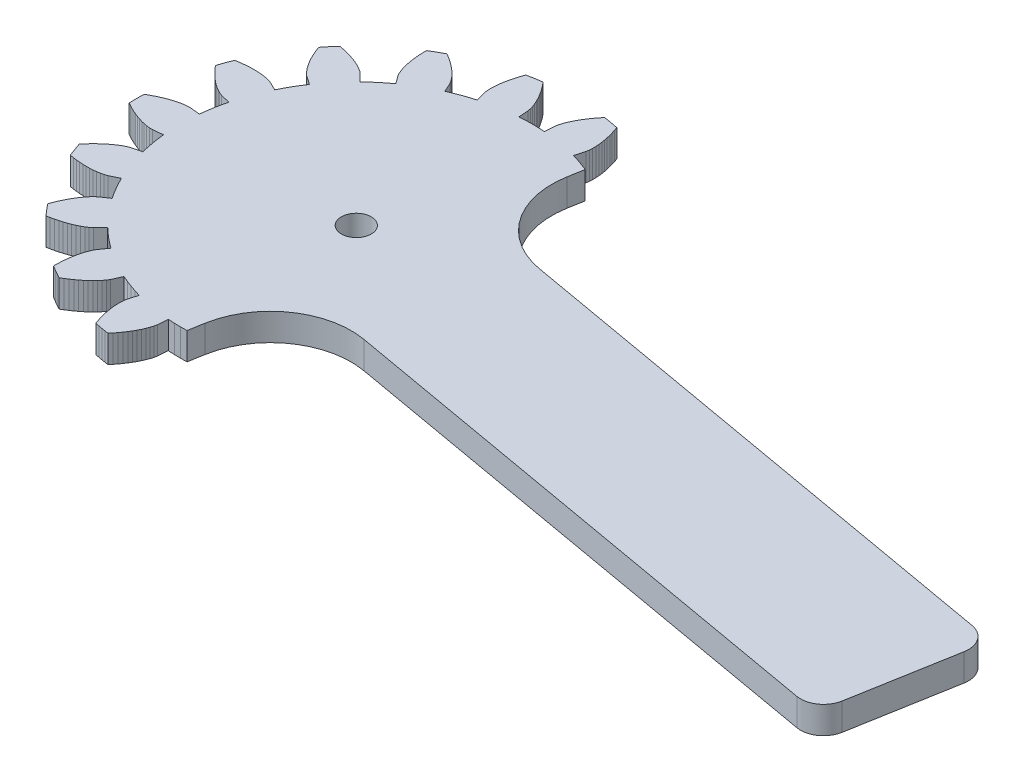
SolidWorks part; units mm, degrees
ref_plane "Front Plane" through (0, 0, 0) normal (0, 0, 1) x (1, 0, 0)
ref_plane "Top Plane" through (0, 0, 0) normal (0, 1, 0) x (1, 0, 0)
ref_plane "Right Plane" through (0, 0, 0) normal (1, 0, 0) x (0, 0, -1)
sketch "Sketch1" plane through (0, 0, 0) normal (0, 1, 0) x (1, 0, 0)
  line L0 (28.4037, 11.9497) -> (144.4799, -8.5177)
  line L1 (148.6006, -14.4026) -> (144.5649, -37.2904)
  line L2 (138.6799, -41.411) -> (22.6037, -20.9437)
  line L3 (0, 0) -> (10.8938, 15.0372) construction
  line L4 (0, 0) -> (5.0938, -17.8562) construction
  line L5 (2.0063, -35.3661) -> (1.4038, -38.7829)
  line L156 (1.4038, -38.7829) -> (0, -38.8083)
  line L157 (0, -38.8083) -> (-1.4038, -38.7829)
  line L158 (-1.4038, -38.7829) -> (-2.8058, -38.7068)
  line L159 (-2.8058, -38.7068) -> (-2.9662, -40.919)
  line L160 (-2.9662, -40.919) -> (-3.0985, -41.5915)
  line L161 (-3.0985, -41.5915) -> (-3.3017, -42.2583)
  line L162 (-3.3017, -42.2583) -> (-3.5532, -42.9207)
  line L163 (-3.5532, -42.9207) -> (-3.8453, -43.5786)
  line L164 (-3.8453, -43.5786) -> (-4.1736, -44.2318)
  line L165 (-4.1736, -44.2318) -> (-4.5353, -44.88)
  line L166 (-4.5353, -44.88) -> (-4.9286, -45.523)
  line L167 (-4.9286, -45.523) -> (-5.3519, -46.1601)
  line L168 (-5.3519, -46.1601) -> (-5.8039, -46.7911)
  line L169 (-5.8039, -46.7911) -> (-6.2839, -47.4155)
  line L170 (-6.2839, -47.4155) -> (-6.7909, -48.0328)
  line L171 (-6.7909, -48.0328) -> (-7.6084, -47.91)
  line L172 (-7.6084, -47.91) -> (-8.4237, -47.7734)
  line L173 (-8.4237, -47.7734) -> (-9.2366, -47.623)
  line L174 (-9.2366, -47.623) -> (-10.0468, -47.4587)
  line L175 (-10.0468, -47.4587) -> (-10.3121, -46.7052)
  line L176 (-10.3121, -46.7052) -> (-10.5496, -45.9543)
  line L177 (-10.5496, -45.9543) -> (-10.7586, -45.2068)
  line L178 (-10.7586, -45.2068) -> (-10.9384, -44.4633)
  line L179 (-10.9384, -44.4633) -> (-11.0881, -43.7246)
  line L180 (-11.0881, -43.7246) -> (-11.2063, -42.9917)
  line L181 (-11.2063, -42.9917) -> (-11.2914, -42.2656)
  line L182 (-11.2914, -42.2656) -> (-11.3408, -41.5475)
  line L183 (-11.3408, -41.5475) -> (-11.3506, -40.8391)
  line L184 (-11.3506, -40.8391) -> (-11.3135, -40.143)
  line L185 (-11.3135, -40.143) -> (-11.2079, -39.4658)
  line L186 (-11.2079, -39.4658) -> (-10.6019, -37.3321)
  line L187 (-10.6019, -37.3321) -> (-11.9454, -36.9242)
  line L188 (-11.9454, -36.9242) -> (-13.2732, -36.4679)
  line L189 (-13.2732, -36.4679) -> (-14.5837, -35.9639)
  line L190 (-14.5837, -35.9639) -> (-15.8751, -35.4128)
  line L191 (-15.8751, -35.4128) -> (-16.7824, -37.4368)
  line L192 (-16.7824, -37.4368) -> (-17.1368, -38.0235)
  line L193 (-17.1368, -38.0235) -> (-17.5558, -38.5806)
  line L194 (-17.5558, -38.5806) -> (-18.0187, -39.117)
  line L195 (-18.0187, -39.117) -> (-18.5181, -39.6353)
  line L196 (-18.5181, -39.6353) -> (-19.05, -40.1368)
  line L197 (-19.05, -40.1368) -> (-19.6117, -40.6222)
  line L198 (-19.6117, -40.6222) -> (-20.2011, -41.0919)
  line L199 (-20.2011, -41.0919) -> (-20.8168, -41.5459)
  line L200 (-20.8168, -41.5459) -> (-21.4574, -41.9842)
  line L201 (-21.4574, -41.9842) -> (-22.122, -42.4068)
  line L202 (-22.122, -42.4068) -> (-22.8095, -42.8134)
  line L203 (-22.8095, -42.8134) -> (-23.5358, -42.4185)
  line L204 (-23.5358, -42.4185) -> (-24.2552, -42.0113)
  line L205 (-24.2552, -42.0113) -> (-24.9676, -41.5918)
  line L206 (-24.9676, -41.5918) -> (-25.6727, -41.1603)
  line L207 (-25.6727, -41.1603) -> (-25.6644, -40.3616)
  line L208 (-25.6644, -40.3616) -> (-25.6307, -39.5748)
  line L209 (-25.6307, -39.5748) -> (-25.5714, -38.8008)
  line L210 (-25.5714, -38.8008) -> (-25.486, -38.0406)
  line L211 (-25.486, -38.0406) -> (-25.3741, -37.2954)
  line L212 (-25.3741, -37.2954) -> (-25.2345, -36.5662)
  line L213 (-25.2345, -36.5662) -> (-25.0661, -35.8548)
  line L214 (-25.0661, -35.8548) -> (-24.8669, -35.1631)
  line L215 (-24.8669, -35.1631) -> (-24.6339, -34.4941)
  line L216 (-24.6339, -34.4941) -> (-24.3609, -33.8526)
  line L217 (-24.3609, -33.8526) -> (-24.03, -33.2524)
  line L218 (-24.03, -33.2524) -> (-22.7309, -31.4547)
  line L219 (-22.7309, -31.4547) -> (-23.8538, -30.6118)
  line L220 (-23.8538, -30.6118) -> (-24.9455, -29.7289)
  line L221 (-24.9455, -29.7289) -> (-26.0046, -28.8071)
  line L222 (-26.0046, -28.8071) -> (-27.0296, -27.8476)
  line L223 (-27.0296, -27.8476) -> (-28.5745, -29.4392)
  line L224 (-28.5745, -29.4392) -> (-29.1081, -29.8693)
  line L225 (-29.1081, -29.8693) -> (-29.6924, -30.2495)
  line L226 (-29.6924, -30.2495) -> (-30.3108, -30.5952)
  line L227 (-30.3108, -30.5952) -> (-30.9574, -30.9114)
  line L228 (-30.9574, -30.9114) -> (-31.6288, -31.2008)
  line L229 (-31.6288, -31.2008) -> (-32.3226, -31.4648)
  line L230 (-32.3226, -31.4648) -> (-33.0371, -31.7046)
  line L231 (-33.0371, -31.7046) -> (-33.7709, -31.9206)
  line L232 (-33.7709, -31.9206) -> (-34.5228, -32.1134)
  line L233 (-34.5228, -32.1134) -> (-35.2918, -32.2831)
  line L234 (-35.2918, -32.2831) -> (-36.077, -32.4301)
  line L235 (-36.077, -32.4301) -> (-36.6244, -31.8106)
  line L236 (-36.6244, -31.8106) -> (-37.1611, -31.1819)
  line L237 (-37.1611, -31.1819) -> (-37.6871, -30.5441)
  line L238 (-37.6871, -30.5441) -> (-38.2021, -29.8975)
  line L239 (-38.2021, -29.8975) -> (-37.9211, -29.1497)
  line L240 (-37.9211, -29.1497) -> (-37.6203, -28.4219)
  line L241 (-37.6203, -28.4219) -> (-37.2999, -27.7149)
  line L242 (-37.2999, -27.7149) -> (-36.9597, -27.0297)
  line L243 (-36.9597, -27.0297) -> (-36.5996, -26.3677)
  line L244 (-36.5996, -26.3677) -> (-36.219, -25.7303)
  line L245 (-36.219, -25.7303) -> (-35.8175, -25.1194)
  line L246 (-35.8175, -25.1194) -> (-35.3938, -24.5375)
  line L247 (-35.3938, -24.5375) -> (-34.9459, -23.9886)
  line L248 (-34.9459, -23.9886) -> (-34.4701, -23.4791)
  line L249 (-34.4701, -23.4791) -> (-33.9538, -23.0283)
  line L250 (-33.9538, -23.0283) -> (-32.1182, -21.7833)
  line L251 (-32.1182, -21.7833) -> (-32.8851, -20.6072)
  line L252 (-32.8851, -20.6072) -> (-33.609, -19.4042)
  line L253 (-33.609, -19.4042) -> (-34.2889, -18.1757)
  line L254 (-34.2889, -18.1757) -> (-34.924, -16.9235)
  line L255 (-34.924, -16.9235) -> (-36.92, -17.8907)
  line L256 (-36.92, -17.8907) -> (-37.5685, -18.1124)
  line L257 (-37.5685, -18.1124) -> (-38.2477, -18.2698)
  line L258 (-38.2477, -18.2698) -> (-38.947, -18.3831)
  line L259 (-38.947, -18.3831) -> (-39.6627, -18.4592)
  line L260 (-39.6627, -18.4592) -> (-40.3926, -18.5015)
  line L261 (-40.3926, -18.5015) -> (-41.1349, -18.5123)
  line L262 (-41.1349, -18.5123) -> (-41.8883, -18.4932)
  line L263 (-41.8883, -18.4932) -> (-42.6518, -18.4452)
  line L264 (-42.6518, -18.4452) -> (-43.4243, -18.3692)
  line L265 (-43.4243, -18.3692) -> (-44.2049, -18.2657)
  line L266 (-44.2049, -18.2657) -> (-44.993, -18.1353)
  line L267 (-44.993, -18.1353) -> (-45.2955, -17.3659)
  line L268 (-45.2955, -17.3659) -> (-45.5849, -16.5915)
  line L269 (-45.5849, -16.5915) -> (-45.861, -15.8123)
  line L270 (-45.861, -15.8123) -> (-46.1238, -15.0285)
  line L271 (-46.1238, -15.0285) -> (-45.604, -14.422)
  line L272 (-45.604, -14.422) -> (-45.0724, -13.841)
  line L273 (-45.0724, -13.841) -> (-44.5295, -13.2862)
  line L274 (-44.5295, -13.2862) -> (-43.9755, -12.7587)
  line L275 (-43.9755, -12.7587) -> (-43.4106, -12.2598)
  line L276 (-43.4106, -12.2598) -> (-42.8351, -11.7909)
  line L277 (-42.8351, -11.7909) -> (-42.2488, -11.3542)
  line L278 (-42.2488, -11.3542) -> (-41.6516, -10.9523)
  line L279 (-41.6516, -10.9523) -> (-41.043, -10.5897)
  line L280 (-41.043, -10.5897) -> (-40.4216, -10.2737)
  line L281 (-40.4216, -10.2737) -> (-39.7823, -10.0266)
  line L282 (-39.7823, -10.0266) -> (-37.6315, -9.4845)
  line L283 (-37.6315, -9.4845) -> (-37.95, -8.1171)
  line L284 (-37.95, -8.1171) -> (-38.2188, -6.739)
  line L285 (-38.2188, -6.739) -> (-38.4375, -5.3521)
  line L286 (-38.4375, -5.3521) -> (-38.606, -3.9582)
  line L287 (-38.606, -3.9582) -> (-40.8125, -4.1844)
  line L288 (-40.8125, -4.1844) -> (-41.4977, -4.1709)
  line L289 (-41.4977, -4.1709) -> (-42.1897, -4.0865)
  line L290 (-42.1897, -4.0865) -> (-42.8856, -3.9538)
  line L291 (-42.8856, -3.9538) -> (-43.5842, -3.7805)
  line L292 (-43.5842, -3.7805) -> (-44.2845, -3.5706)
  line L293 (-44.2845, -3.5706) -> (-44.9857, -3.3269)
  line L294 (-44.9857, -3.3269) -> (-45.6872, -3.0513)
  line L295 (-45.6872, -3.0513) -> (-46.3882, -2.7451)
  line L296 (-46.3882, -2.7451) -> (-47.0881, -2.4094)
  line L297 (-47.0881, -2.4094) -> (-47.7863, -2.0452)
  line L298 (-47.7863, -2.0452) -> (-48.4823, -1.6531)
  line L299 (-48.4823, -1.6531) -> (-48.5034, -0.8267)
  line L300 (-48.5034, -0.8267) -> (-48.5104, 0)
  line L301 (-48.5104, 0) -> (-48.5034, 0.8267)
  line L302 (-48.5034, 0.8267) -> (-48.4823, 1.6531)
  line L303 (-48.4823, 1.6531) -> (-47.7863, 2.0452)
  line L304 (-47.7863, 2.0452) -> (-47.0881, 2.4094)
  line L305 (-47.0881, 2.4094) -> (-46.3882, 2.7451)
  line L306 (-46.3882, 2.7451) -> (-45.6872, 3.0513)
  line L307 (-45.6872, 3.0513) -> (-44.9857, 3.3269)
  line L308 (-44.9857, 3.3269) -> (-44.2845, 3.5706)
  line L309 (-44.2845, 3.5706) -> (-43.5842, 3.7805)
  line L310 (-43.5842, 3.7805) -> (-42.8856, 3.9538)
  line L311 (-42.8856, 3.9538) -> (-42.1897, 4.0865)
  line L312 (-42.1897, 4.0865) -> (-41.4977, 4.1709)
  line L313 (-41.4977, 4.1709) -> (-40.8125, 4.1844)
  line L314 (-40.8125, 4.1844) -> (-38.606, 3.9582)
  line L315 (-38.606, 3.9582) -> (-38.4375, 5.3521)
  line L316 (-38.4375, 5.3521) -> (-38.2188, 6.739)
  line L317 (-38.2188, 6.739) -> (-37.95, 8.1171)
  line L318 (-37.95, 8.1171) -> (-37.6315, 9.4845)
  line L319 (-37.6315, 9.4845) -> (-39.7823, 10.0266)
  line L320 (-39.7823, 10.0266) -> (-40.4216, 10.2737)
  line L321 (-40.4216, 10.2737) -> (-41.043, 10.5897)
  line L322 (-41.043, 10.5897) -> (-41.6516, 10.9523)
  line L323 (-41.6516, 10.9523) -> (-42.2488, 11.3542)
  line L324 (-42.2488, 11.3542) -> (-42.8351, 11.7909)
  line L325 (-42.8351, 11.7909) -> (-43.4106, 12.2598)
  line L326 (-43.4106, 12.2598) -> (-43.9755, 12.7587)
  line L327 (-43.9755, 12.7587) -> (-44.5295, 13.2862)
  line L328 (-44.5295, 13.2862) -> (-45.0724, 13.841)
  line L329 (-45.0724, 13.841) -> (-45.604, 14.422)
  line L330 (-45.604, 14.422) -> (-46.1238, 15.0285)
  line L331 (-46.1238, 15.0285) -> (-45.861, 15.8123)
  line L332 (-45.861, 15.8123) -> (-45.5849, 16.5915)
  line L333 (-45.5849, 16.5915) -> (-45.2955, 17.3659)
  line L334 (-45.2955, 17.3659) -> (-44.993, 18.1353)
  line L335 (-44.993, 18.1353) -> (-44.2049, 18.2657)
  line L336 (-44.2049, 18.2657) -> (-43.4243, 18.3692)
  line L337 (-43.4243, 18.3692) -> (-42.6518, 18.4452)
  line L338 (-42.6518, 18.4452) -> (-41.8883, 18.4932)
  line L339 (-41.8883, 18.4932) -> (-41.1349, 18.5123)
  line L340 (-41.1349, 18.5123) -> (-40.3926, 18.5015)
  line L341 (-40.3926, 18.5015) -> (-39.6627, 18.4592)
  line L342 (-39.6627, 18.4592) -> (-38.947, 18.3831)
  line L343 (-38.947, 18.3831) -> (-38.2477, 18.2698)
  line L344 (-38.2477, 18.2698) -> (-37.5685, 18.1124)
  line L345 (-37.5685, 18.1124) -> (-36.92, 17.8907)
  line L346 (-36.92, 17.8907) -> (-34.924, 16.9235)
  line L347 (-34.924, 16.9235) -> (-34.2889, 18.1757)
  line L348 (-34.2889, 18.1757) -> (-33.609, 19.4042)
  line L349 (-33.609, 19.4042) -> (-32.8851, 20.6072)
  line L350 (-32.8851, 20.6072) -> (-32.1182, 21.7833)
  line L351 (-32.1182, 21.7833) -> (-33.9538, 23.0283)
  line L352 (-33.9538, 23.0283) -> (-34.4701, 23.4791)
  line L353 (-34.4701, 23.4791) -> (-34.9459, 23.9886)
  line L354 (-34.9459, 23.9886) -> (-35.3938, 24.5375)
  line L355 (-35.3938, 24.5375) -> (-35.8175, 25.1194)
  line L356 (-35.8175, 25.1194) -> (-36.219, 25.7303)
  line L357 (-36.219, 25.7303) -> (-36.5996, 26.3677)
  line L358 (-36.5996, 26.3677) -> (-36.9597, 27.0297)
  line L359 (-36.9597, 27.0297) -> (-37.2999, 27.7149)
  line L360 (-37.2999, 27.7149) -> (-37.6203, 28.4219)
  line L361 (-37.6203, 28.4219) -> (-37.9211, 29.1497)
  line L362 (-37.9211, 29.1497) -> (-38.2021, 29.8975)
  line L363 (-38.2021, 29.8975) -> (-37.6871, 30.5441)
  line L364 (-37.6871, 30.5441) -> (-37.1611, 31.1819)
  line L365 (-37.1611, 31.1819) -> (-36.6244, 31.8106)
  line L366 (-36.6244, 31.8106) -> (-36.077, 32.4301)
  line L367 (-36.077, 32.4301) -> (-35.2918, 32.2831)
  line L368 (-35.2918, 32.2831) -> (-34.5228, 32.1134)
  line L369 (-34.5228, 32.1134) -> (-33.7709, 31.9206)
  line L370 (-33.7709, 31.9206) -> (-33.0371, 31.7046)
  line L371 (-33.0371, 31.7046) -> (-32.3226, 31.4648)
  line L372 (-32.3226, 31.4648) -> (-31.6288, 31.2008)
  line L373 (-31.6288, 31.2008) -> (-30.9574, 30.9114)
  line L374 (-30.9574, 30.9114) -> (-30.3108, 30.5952)
  line L375 (-30.3108, 30.5952) -> (-29.6924, 30.2495)
  line L376 (-29.6924, 30.2495) -> (-29.1081, 29.8693)
  line L377 (-29.1081, 29.8693) -> (-28.5745, 29.4392)
  line L378 (-28.5745, 29.4392) -> (-27.0296, 27.8476)
  line L379 (-27.0296, 27.8476) -> (-26.0046, 28.8071)
  line L380 (-26.0046, 28.8071) -> (-24.9455, 29.7289)
  line L381 (-24.9455, 29.7289) -> (-23.8538, 30.6118)
  line L382 (-23.8538, 30.6118) -> (-22.7309, 31.4547)
  line L383 (-22.7309, 31.4547) -> (-24.03, 33.2524)
  line L384 (-24.03, 33.2524) -> (-24.3609, 33.8526)
  line L385 (-24.3609, 33.8526) -> (-24.6339, 34.4941)
  line L386 (-24.6339, 34.4941) -> (-24.8669, 35.1631)
  line L387 (-24.8669, 35.1631) -> (-25.0661, 35.8548)
  line L388 (-25.0661, 35.8548) -> (-25.2345, 36.5662)
  line L389 (-25.2345, 36.5662) -> (-25.3741, 37.2954)
  line L390 (-25.3741, 37.2954) -> (-25.486, 38.0406)
  line L391 (-25.486, 38.0406) -> (-25.5714, 38.8008)
  line L392 (-25.5714, 38.8008) -> (-25.6307, 39.5748)
  line L393 (-25.6307, 39.5748) -> (-25.6644, 40.3616)
  line L394 (-25.6644, 40.3616) -> (-25.6727, 41.1603)
  line L395 (-25.6727, 41.1603) -> (-24.9676, 41.5918)
  line L396 (-24.9676, 41.5918) -> (-24.2552, 42.0113)
  line L397 (-24.2552, 42.0113) -> (-23.5358, 42.4185)
  line L398 (-23.5358, 42.4185) -> (-22.8095, 42.8134)
  line L399 (-22.8095, 42.8134) -> (-22.122, 42.4068)
  line L400 (-22.122, 42.4068) -> (-21.4574, 41.9842)
  line L401 (-21.4574, 41.9842) -> (-20.8168, 41.5459)
  line L402 (-20.8168, 41.5459) -> (-20.2011, 41.0919)
  line L403 (-20.2011, 41.0919) -> (-19.6117, 40.6222)
  line L404 (-19.6117, 40.6222) -> (-19.05, 40.1368)
  line L405 (-19.05, 40.1368) -> (-18.5181, 39.6353)
  line L406 (-18.5181, 39.6353) -> (-18.0187, 39.117)
  line L407 (-18.0187, 39.117) -> (-17.5558, 38.5806)
  line L408 (-17.5558, 38.5806) -> (-17.1368, 38.0235)
  line L409 (-17.1368, 38.0235) -> (-16.7824, 37.4368)
  line L410 (-16.7824, 37.4368) -> (-15.8751, 35.4128)
  line L411 (-15.8751, 35.4128) -> (-14.5837, 35.9639)
  line L412 (-14.5837, 35.9639) -> (-13.2732, 36.4679)
  line L413 (-13.2732, 36.4679) -> (-11.9454, 36.9242)
  line L414 (-11.9454, 36.9242) -> (-10.6019, 37.3321)
  line L415 (-10.6019, 37.3321) -> (-11.2079, 39.4658)
  line L416 (-11.2079, 39.4658) -> (-11.3135, 40.143)
  line L417 (-11.3135, 40.143) -> (-11.3506, 40.8391)
  line L418 (-11.3506, 40.8391) -> (-11.3408, 41.5475)
  line L419 (-11.3408, 41.5475) -> (-11.2914, 42.2656)
  line L420 (-11.2914, 42.2656) -> (-11.2063, 42.9917)
  line L421 (-11.2063, 42.9917) -> (-11.0881, 43.7246)
  line L422 (-11.0881, 43.7246) -> (-10.9384, 44.4633)
  line L423 (-10.9384, 44.4633) -> (-10.7586, 45.2068)
  line L424 (-10.7586, 45.2068) -> (-10.5496, 45.9543)
  line L425 (-10.5496, 45.9543) -> (-10.3121, 46.7052)
  line L426 (-10.3121, 46.7052) -> (-10.0468, 47.4587)
  line L427 (-10.0468, 47.4587) -> (-9.2366, 47.623)
  line L428 (-9.2366, 47.623) -> (-8.4237, 47.7734)
  line L429 (-8.4237, 47.7734) -> (-7.6084, 47.91)
  line L430 (-7.6084, 47.91) -> (-6.7909, 48.0328)
  line L431 (-6.7909, 48.0328) -> (-6.2839, 47.4155)
  line L432 (-6.2839, 47.4155) -> (-5.8039, 46.7911)
  line L433 (-5.8039, 46.7911) -> (-5.3519, 46.1601)
  line L434 (-5.3519, 46.1601) -> (-4.9286, 45.523)
  line L435 (-4.9286, 45.523) -> (-4.5353, 44.88)
  line L436 (-4.5353, 44.88) -> (-4.1736, 44.2318)
  line L437 (-4.1736, 44.2318) -> (-3.8453, 43.5786)
  line L438 (-3.8453, 43.5786) -> (-3.5532, 42.9207)
  line L439 (-3.5532, 42.9207) -> (-3.3017, 42.2583)
  line L440 (-3.3017, 42.2583) -> (-3.0985, 41.5915)
  line L441 (-3.0985, 41.5915) -> (-2.9662, 40.919)
  line L442 (-2.9662, 40.919) -> (-2.8058, 38.7068)
  line L443 (-2.8058, 38.7068) -> (-1.4038, 38.7829)
  line L444 (-1.4038, 38.7829) -> (0, 38.8083)
  line L445 (0, 38.8083) -> (1.4038, 38.7829)
  line L446 (1.4038, 38.7829) -> (2.8058, 38.7068)
  line L447 (2.8058, 38.7068) -> (2.9662, 40.919)
  line L448 (2.9662, 40.919) -> (3.0985, 41.5915)
  line L449 (3.0985, 41.5915) -> (3.3017, 42.2583)
  line L450 (3.3017, 42.2583) -> (3.5532, 42.9207)
  line L451 (3.5532, 42.9207) -> (3.8453, 43.5786)
  line L452 (3.8453, 43.5786) -> (4.1736, 44.2318)
  line L453 (4.1736, 44.2318) -> (4.5353, 44.88)
  line L454 (4.5353, 44.88) -> (4.9286, 45.523)
  line L455 (4.9286, 45.523) -> (5.3519, 46.1601)
  line L456 (5.3519, 46.1601) -> (5.8039, 46.7911)
  line L457 (5.8039, 46.7911) -> (6.2839, 47.4155)
  line L458 (6.2839, 47.4155) -> (6.7909, 48.0328)
  line L459 (6.7909, 48.0328) -> (7.6084, 47.91)
  line L460 (7.6084, 47.91) -> (8.4237, 47.7734)
  line L461 (8.4237, 47.7734) -> (9.2366, 47.623)
  line L462 (9.2366, 47.623) -> (10.0468, 47.4587)
  line L463 (10.0468, 47.4587) -> (10.3121, 46.7052)
  line L464 (10.3121, 46.7052) -> (10.5496, 45.9543)
  line L465 (10.5496, 45.9543) -> (10.7586, 45.2068)
  line L466 (10.7586, 45.2068) -> (10.9384, 44.4633)
  line L467 (10.9384, 44.4633) -> (11.0881, 43.7246)
  line L468 (11.0881, 43.7246) -> (11.2063, 42.9917)
  line L469 (11.2063, 42.9917) -> (11.2914, 42.2656)
  line L470 (11.2914, 42.2656) -> (11.3408, 41.5475)
  line L471 (11.3408, 41.5475) -> (11.3506, 40.8391)
  line L472 (11.3506, 40.8391) -> (11.3135, 40.143)
  line L473 (11.3135, 40.143) -> (11.2079, 39.4658)
  line L474 (11.2079, 39.4658) -> (10.6019, 37.3321)
  line L475 (10.6019, 37.3321) -> (11.9454, 36.9242)
  line L476 (11.9454, 36.9242) -> (13.2732, 36.4679)
  line L477 (13.2732, 36.4679) -> (14.5837, 35.9639)
  line L478 (14.5837, 35.9639) -> (13.9812, 32.547)
  circle A0 centre (0, 0) radius 3.3
  arc A1 (28.4037, 11.9497) -> (13.9812, 32.547) centre (31.4911, 29.4596) cw
  arc A2 (22.6037, -20.9437) -> (2.0063, -35.3661) centre (19.5162, -38.4535) ccw
  arc A3 (144.5649, -37.2904) -> (138.6799, -41.411) centre (139.562, -36.4082) cw
  arc A4 (144.4799, -8.5177) -> (148.6006, -14.4026) centre (143.5978, -13.5205) cw
  dimension "D1" = 17.78
  dimension "D2" = 17.78
  dimension "D3" = 5.08
extrude "Boss-Extrude1" add sketch "Sketch1" along normal blind 6
